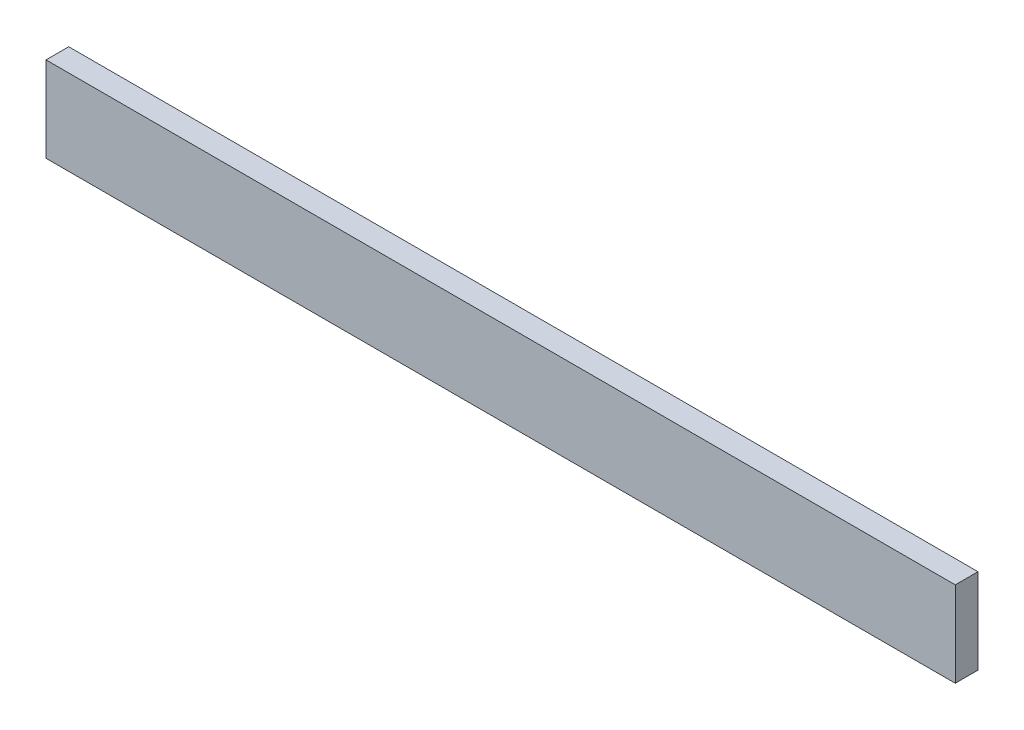
SolidWorks part; units mm, degrees
ref_plane "Front Plane" through (0, 0, 0) normal (0, 0, 1) x (1, 0, 0)
ref_plane "Top Plane" through (0, 0, 0) normal (0, 1, 0) x (1, 0, 0)
ref_plane "Right Plane" through (0, 0, 0) normal (1, 0, 0) x (0, 0, -1)
sketch "Sketch1" plane through (0, 0, 0) normal (0, 0, 1) x (1, 0, 0)
  line L0 (0, -225.635) -> (0, 232.62) construction
  line L1 (50.8, 232.62) -> (-50.8, 232.62)
  line L2 (50.8, 232.62) -> (50.8, 242.145)
  line L3 (50.8, 242.145) -> (-50.8, 242.145)
  line L4 (-50.8, 232.62) -> (-50.8, 242.145)
  line L5 (-225.635, -225.635) -> (225.635, -225.635) construction
  line L6 (0, 232.62) -> (0, 242.145) construction
  line L7 (257.385, 251.035) -> (-257.385, 251.035) construction
  dimension "D1" = 9.525
  dimension "D2" = 101.6
  dimension "D3" = 8.89
extrude "Extrude1" add sketch "Sketch1" along normal blind 2.54
